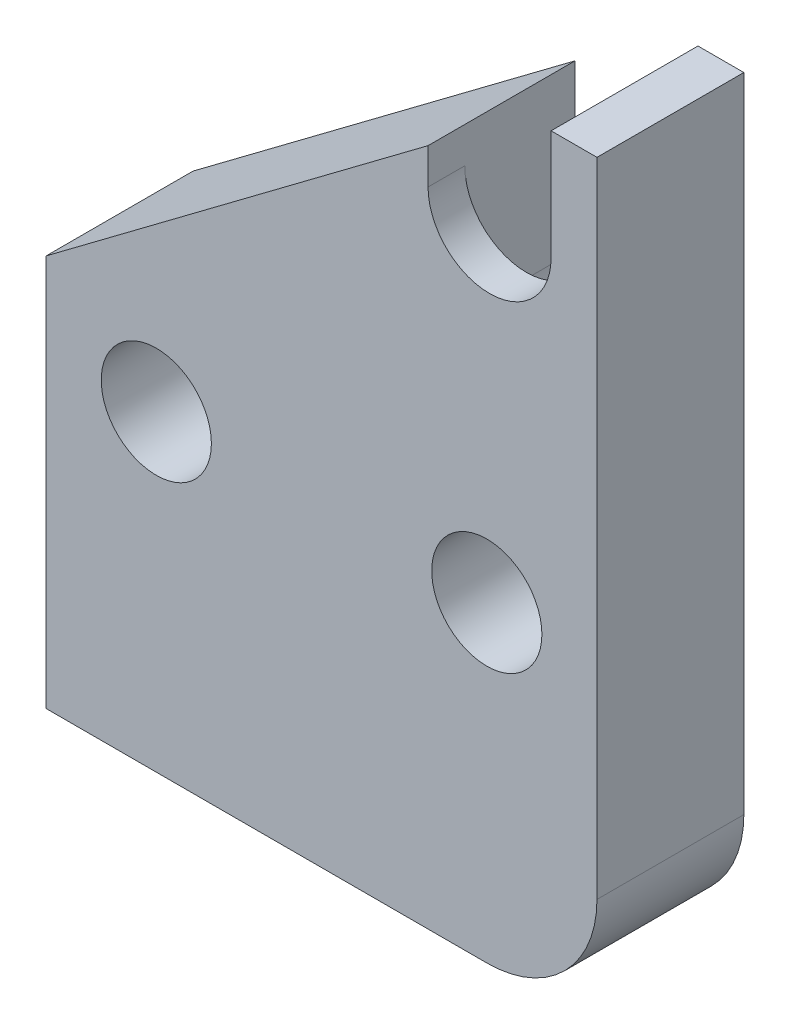
SolidWorks part; units mm, degrees
ref_plane "Front" through (0, 0, 0) normal (0, 0, 1) x (1, 0, 0)
ref_plane "Top" through (0, 0, 0) normal (0, 1, 0) x (1, 0, 0)
ref_plane "Right" through (0, 0, 0) normal (1, 0, 0) x (0, 0, -1)
sketch "Sketch1" plane through (0, 0, 0) normal (0, 0, 1) x (1, 0, 0)
  line L0 (0, 20.5) -> (0, 0)
  line L1 (0, 0) -> (-15, 0)
  line L2 (-15, 0) -> (-15, 10.675)
  line L3 (-15, 10.675) -> (-1.9, 20.5)
  line L4 (-1.9, 20.5) -> (0, 20.5)
  dimension "D1" = 20.5
  dimension "D2" = 15
  dimension "D3" = 1.9
  dimension "D4" = 10.675
extrude "Extrude1" add sketch "Sketch1" along normal blind 4
sketch "Sketch2" plane through (0, 0, 0) normal (0, 0, -1) x (-1, 0, 0)
  line L0 (0, 0) -> (0, 20.5) construction
  line L1 (15, 0) -> (0, 0) construction
  line L2 (0.4, 14) -> (0.4, 21.5254)
  line L3 (0.4, 21.5254) -> (4.6, 21.5254)
  line L4 (4.6, 21.5254) -> (4.6, 14)
  arc A0 (4.6, 14) -> (0.4, 14) centre (2.5, 14) cw
  dimension "D1" = 2.1
  dimension "D2" = 2.5
  dimension "D3" = 14
extrude "Extrude2" cut sketch "Sketch2" against normal blind 3
sketch "Sketch4" plane through (0, 0, 4) normal (0, 0, 1) x (1, 0, 0)
  line L1 (0, 0) -> (0, 20.5) construction
  line L2 (-15, 0) -> (0, 0) construction
  circle A0 centre (-3, 8.5) radius 1.5
  circle A1 centre (-12, 8.5) radius 1.5
  dimension "D4" = 3
  dimension "D5" = 3
  dimension "D1" = 3
  dimension "D2" = 9
  dimension "D3" = 8.5
extrude "Extrude3" cut sketch "Sketch4" against normal up to surface (4 mm away) up to face at (-5, 12.0062, 0)
fillet "Fillet3" radius 3 1 edges at (0, 0, 2)
sketch "Sketch5" plane through (0, 0, 4) normal (0, 0, 1) x (1, 0, 0)
  line L0 (-1.25, 23.3867) -> (-1.25, 17.5)
  line L1 (-4.6, 17.5) -> (-4.6, 23.3867)
  line L2 (-4.6, 23.3867) -> (-1.25, 23.3867)
  line L5 (0, 3) -> (0, 20.5) construction
  line L6 (0, 20.5) -> (-1.9, 20.5) construction
  arc A0 (-1.25, 17.5) -> (-4.6, 17.5) centre (-2.925, 17.5) cw
  dimension "D1" = 1.25
  dimension "D2" = 3
  dimension "D3" = 3.35
extrude "Extrude4" cut sketch "Sketch5" against normal up to surface (4 mm away) up to face at (-13.5, 8.5, 0)
sketch "Sketch8" plane through (0, 0, 0) normal (0, 0, -1) x (-1, 0, 0)
  line L0 (0.4, 20.5) -> (1.25, 20.5)
  line L1 (1.25, 20.5) -> (1.25, 15.6875)
  line L2 (0.4, 20.5) -> (0.4, 14)
  arc A1 (0.4, 14) -> (1.25, 15.6875) centre (2.5, 14) cw
extrude "Extrude6" add sketch "Sketch8" against normal up to surface (3 mm away) up to face at (-2.0833, 16.7042, 3)
